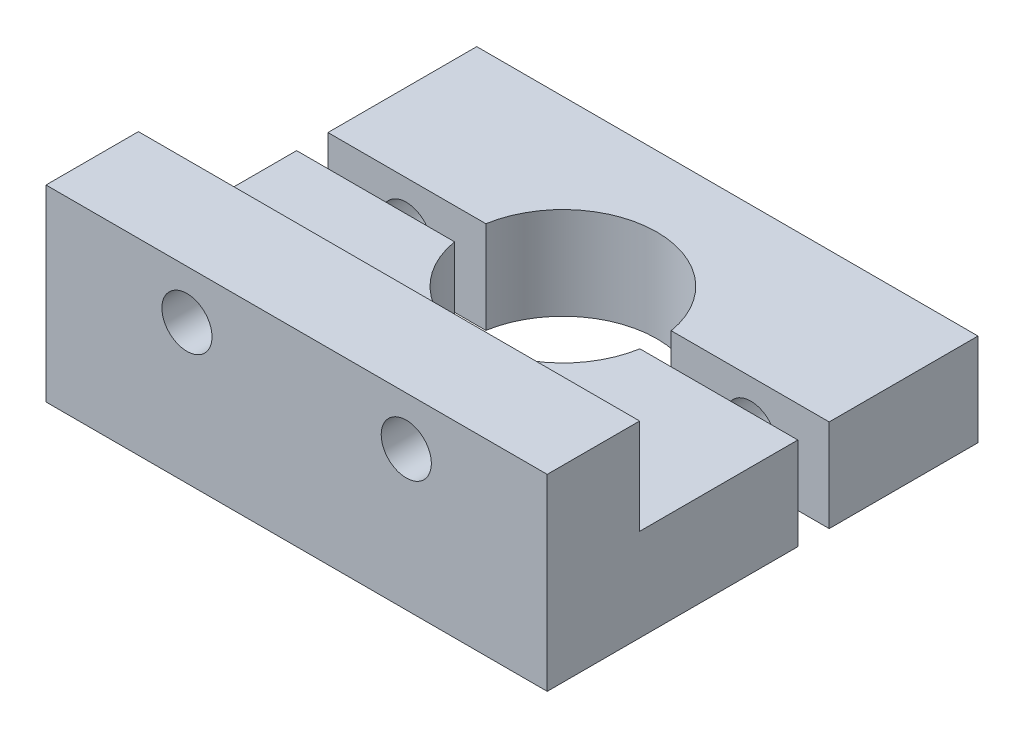
SolidWorks part; units mm, degrees
ref_plane "前视基准面" through (0, 0, 0) normal (0, 0, 1) x (1, 0, 0)
ref_plane "上视基准面" through (0, 0, 0) normal (0, 1, 0) x (1, 0, 0)
ref_plane "右视基准面" through (0, 0, 0) normal (1, 0, 0) x (0, 0, -1)
other "Configuration Table"
sketch "草图1" plane through (0, 0, 0) normal (0, 1, 0) x (1, 0, 0)
  line L0 (0, 0) -> (0, 56.3917) construction
  line L1 (-16, 0) -> (16, 0)
  line L2 (16, 0) -> (16, 16)
  line L3 (16, 16) -> (-16, 16)
  line L4 (-16, 0) -> (-16, 16)
  line L5 (0, 17) -> (19.6965, 17) construction
  line L6 (16.0026, 18) -> (-16, 18)
  line L7 (-16, 18) -> (-16, 27.5)
  line L8 (-16, 27.5) -> (16.0026, 27.5)
  line L9 (16.0026, 27.5) -> (16.0026, 18)
  circle A0 centre (0, 17) radius 6
  dimension "D3" = 12
  dimension "D1" = 32
  dimension "D2" = 16
  dimension "D4" = 9.5
  dimension "D5" = 2
extrude "凸台-拉伸1" add sketch "草图1" along normal mid plane 5.9 contours A0 L3 L4 L1 L2 | A0 L6 L9 L8 L7
sketch "草图3" plane through (0, 0, -27.5) normal (0, 0, -1) x (-1, 0, 0)
  line L1 (-19.1253, 0) -> (19.9984, 0) construction
  line L2 (0, 0) -> (0, 7.6706) construction
  circle A0 centre (-11, 0) radius 1.6
  circle A1 centre (11, 0) radius 1.6
  dimension "D1" = 3.2
  dimension "D2" = 22
extrude "切除-拉伸1" cut sketch "草图3" against normal blind 17.5
sketch "草图4" plane through (0, 2.95, 0) normal (0, 1, 0) x (1, 0, 0)
  line L0 (-16, 5.9) -> (16, 5.9)
  line L1 (-16, 0) -> (-16, 16) construction
  line L2 (16, 0) -> (16, 16) construction
  line L3 (16, 5.9) -> (16, 0)
  line L4 (16, 0) -> (-16, 0)
  line L5 (-16, 0) -> (-16, 5.9)
  dimension "D1" = 5.9
extrude "凸台-拉伸2" add sketch "草图4" along normal blind 6.1
sketch "草图5" plane through (0, 0, -5.9) normal (0, 0, -1) x (-1, 0, 0)
  line L0 (0, 0) -> (0, 11.9964) construction
  line L1 (-17.9508, 5.95) -> (18.1267, 5.95) construction
  line L2 (-16, 9.05) -> (16, 9.05) construction
  circle A0 centre (-7, 5.95) radius 1.6
  circle A1 centre (7, 5.95) radius 1.6
  dimension "D2" = 3.2
  dimension "D1" = 3.1
  dimension "D3" = 14
extrude "切除-拉伸2" cut sketch "草图5" against normal blind 6.1
